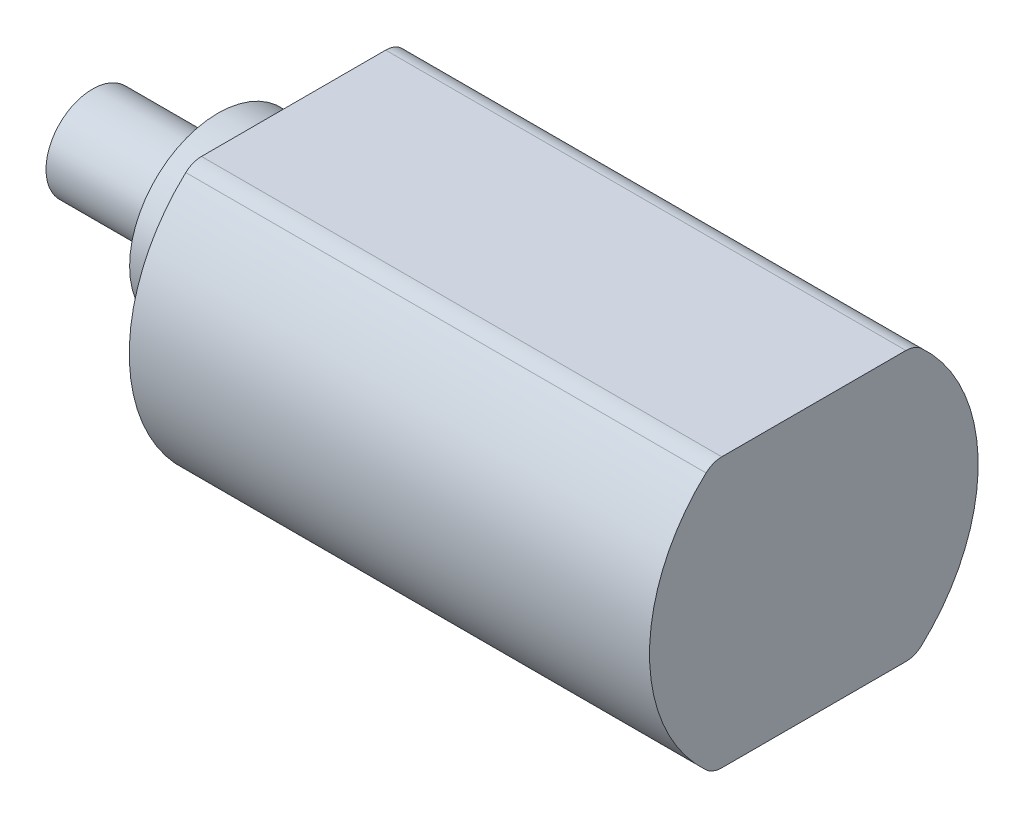
SolidWorks part; units mm, degrees
ref_plane "Front Plane" through (0, 0, 0) normal (0, 0, 1) x (1, 0, 0)
ref_plane "Top Plane" through (0, 0, 0) normal (0, 1, 0) x (1, 0, 0)
ref_plane "Right Plane" through (0, 0, 0) normal (1, 0, 0) x (0, 0, -1)
sketch "Sketch1" plane through (0, 0, 0) normal (1, 0, 0) x (0, 0, -1)
  line L0 (-11.0194, 14.732) -> (11.0194, 14.732)
  line L1 (-11.0194, 14.732) -> (-11.0194, -14.732) construction
  line L2 (-11.0194, -14.732) -> (11.0194, -14.732)
  line L3 (11.0194, -14.732) -> (11.0194, 14.732) construction
  line L4 (1.1164, 0) -> (-1.1164, 0) construction
  arc A0 (-11.0194, 14.732) -> (-11.0194, -14.732) centre (1.1164, 0) ccw
  arc A1 (11.0194, 14.732) -> (11.0194, -14.732) centre (-1.1164, 0) cw
  point P4 (0, 14.732)
  point P5 (11.0194, 0)
  point P8 (0, 0)
  point P10 (-17.9705, 0)
  point P11 (17.9705, 0)
  dimension "D1" = 35.941
  dimension "D2" = 29.464
extrude "Boss-Extrude1" add sketch "Sketch1" along normal blind 56.896
fillet "Fillet1" radius 2.54 2 edges at (28.448, -14.732, 11.0194) (28.448, -14.732, -11.0194)
fillet "Fillet2" radius 2.54 2 edges at (28.448, 14.732, 11.0194) (28.448, 14.732, -11.0194)
sketch "Sketch2" plane through (0, 0, 0) normal (-1, 0, 0) x (0, 0, 1)
  circle A0 centre (0, 0) radius 9.652
  dimension "D1" = 19.304
extrude "Boss-Extrude2" add sketch "Sketch2" along normal blind 8.2804
sketch "Sketch3" plane through (-8.2804, 0, 0) normal (-1, 0, 0) x (0, 0, 1)
  circle A0 centre (0, 0) radius 5.08
  dimension "D1" = 10.16
extrude "Boss-Extrude3" add sketch "Sketch3" along normal blind 13.716
